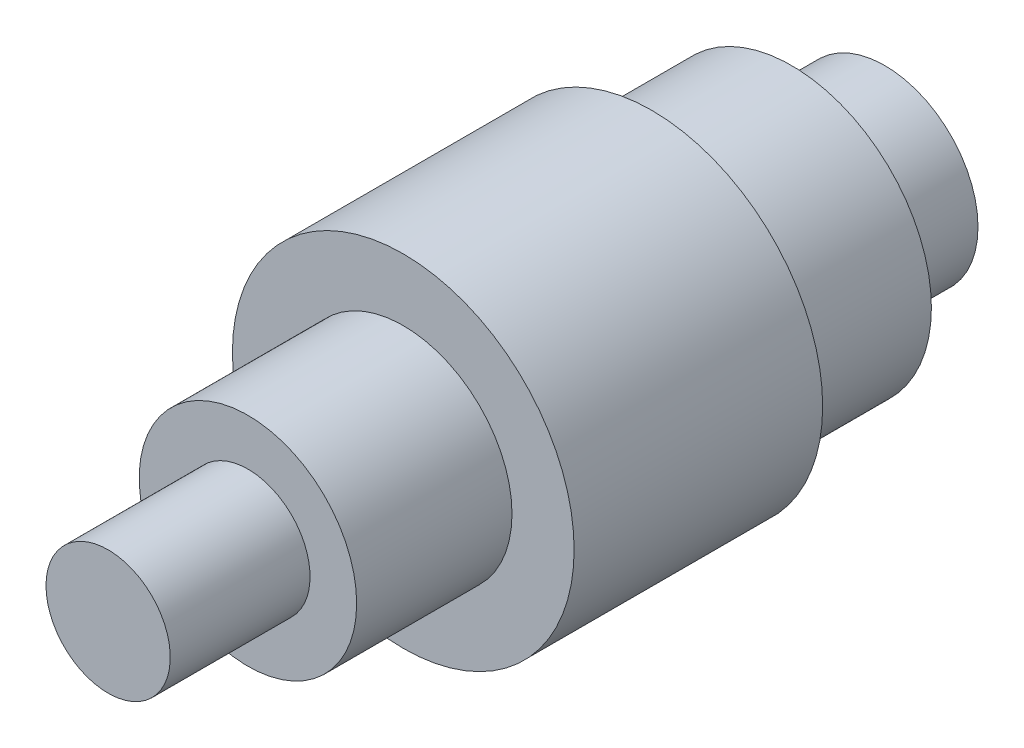
SolidWorks part; units mm, degrees
ref_plane "Plano frontal" through (0, 0, 0) normal (0, 0, 1) x (1, 0, 0)
ref_plane "Plano superior" through (0, 0, 0) normal (0, 1, 0) x (1, 0, 0)
ref_plane "Plano direito" through (0, 0, 0) normal (1, 0, 0) x (0, 0, -1)
sketch "Esboço1" plane through (0, 0, 0) normal (0, 0, 1) x (1, 0, 0)
  circle A0 centre (0, 0) radius 30
  dimension "D1" = 60
extrude "Ressalto-extrusão1" add sketch "Esboço1" along normal blind 30
sketch "Esboço2" plane through (0, 0, 30) normal (0, 0, 1) x (1, 0, 0)
  circle A0 centre (0, 0) radius 45
  dimension "D1" = 90
extrude "Ressalto-extrusão3" add sketch "Esboço2" along normal blind 45
sketch "Esboço3" plane through (0, 0, 75) normal (0, 0, 1) x (1, 0, 0)
  circle A0 centre (0, 0) radius 55
  dimension "D1" = 110
extrude "Ressalto-extrusão4" add sketch "Esboço3" along normal blind 80
sketch "Esboço4" plane through (0, 0, 155) normal (0, 0, 1) x (1, 0, 0)
  circle A0 centre (0, 0) radius 35
  dimension "D1" = 70
extrude "Ressalto-extrusão5" add sketch "Esboço4" along normal blind 50
sketch "Esboço5" plane through (0, 0, 205) normal (0, 0, 1) x (1, 0, 0)
  circle A0 centre (0, 0) radius 20
  dimension "D1" = 40
extrude "Ressalto-extrusão6" add sketch "Esboço5" along normal blind 45
